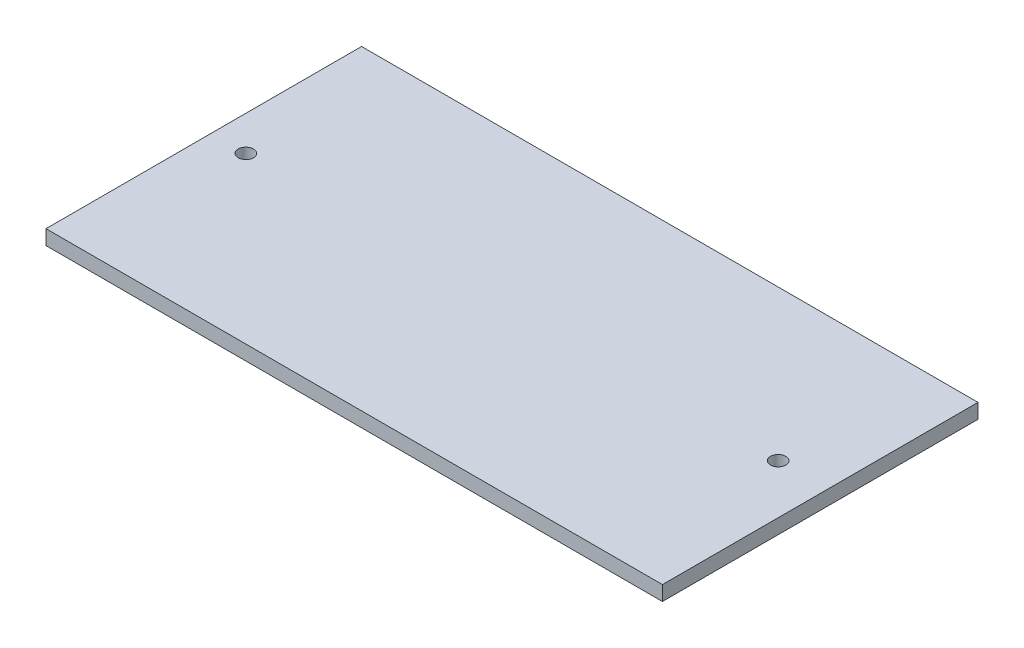
SolidWorks part; units mm, degrees
ref_plane "Front Plane" through (0, 0, 0) normal (0, 0, 1) x (1, 0, 0)
ref_plane "Top Plane" through (0, 0, 0) normal (0, 1, 0) x (1, 0, 0)
ref_plane "Right Plane" through (0, 0, 0) normal (1, 0, 0) x (0, 0, -1)
sketch "Sketch1" plane through (0, 0, 0) normal (0, 1, 0) x (1, 0, 0)
  line L0 (0, 34.0875) -> (0, -34.0875) construction
  line L1 (-66.5875, 34.0875) -> (66.5875, 34.0875)
  line L2 (-66.5875, 34.0875) -> (-66.5875, -34.0875)
  line L3 (-66.5875, -34.0875) -> (66.5875, -34.0875)
  line L4 (66.5875, 34.0875) -> (66.5875, -34.0875)
  line L5 (-66.5875, 34.0875) -> (66.5875, -34.0875) construction
  line L6 (-66.5875, -34.0875) -> (66.5875, 34.0875) construction
  line L7 (-59.0875, 26.5875) -> (55.9125, 26.5875) construction
  line L8 (-59.0875, 26.5875) -> (-59.0875, -23.4125) construction
  line L9 (-59.0875, -23.4125) -> (55.9125, -23.4125) construction
  line L10 (55.9125, 26.5875) -> (55.9125, -23.4125) construction
  line L11 (-66.5875, 0) -> (66.5875, 0) construction
  circle A1 centre (-59.0875, 1.5875) radius 1.65
  circle A2 centre (55.9125, 1.5875) radius 1.65
  point P0 (0, 0)
  point P6 (0, 0)
  point P23 (0, 0)
  point P24 (0, 0)
  dimension "D1" = 133.175
  dimension "D2" = 7.5
  dimension "D3" = 7.5
  dimension "D4" = 10.675
  dimension "D5" = 10.675
  dimension "D6" = 68.175
extrude "Boss-Extrude1" add sketch "Sketch1" along normal blind 3.175
